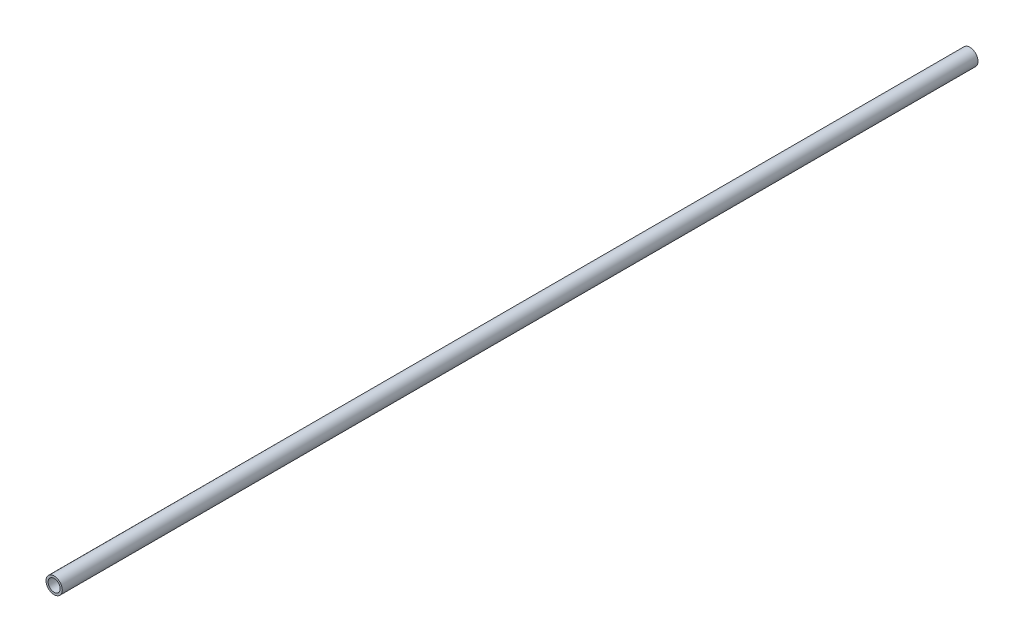
SolidWorks part; units mm, degrees
ref_plane "Front Plane" through (0, 0, 0) normal (0, 0, 1) x (1, 0, 0)
ref_plane "Top Plane" through (0, 0, 0) normal (0, 1, 0) x (1, 0, 0)
ref_plane "Right Plane" through (0, 0, 0) normal (1, 0, 0) x (0, 0, -1)
sketch "Sketch1" plane through (0, 0, 0) normal (0, 0, 1) x (1, 0, 0)
  circle A0 centre (0, 0) radius 10.668
  dimension "Pipe OD" = 21.336
extrude "Extrude-Thin1" add sketch "Sketch1" along normal mid plane 1200 thin thin type one direction reverse wall 2.7686
